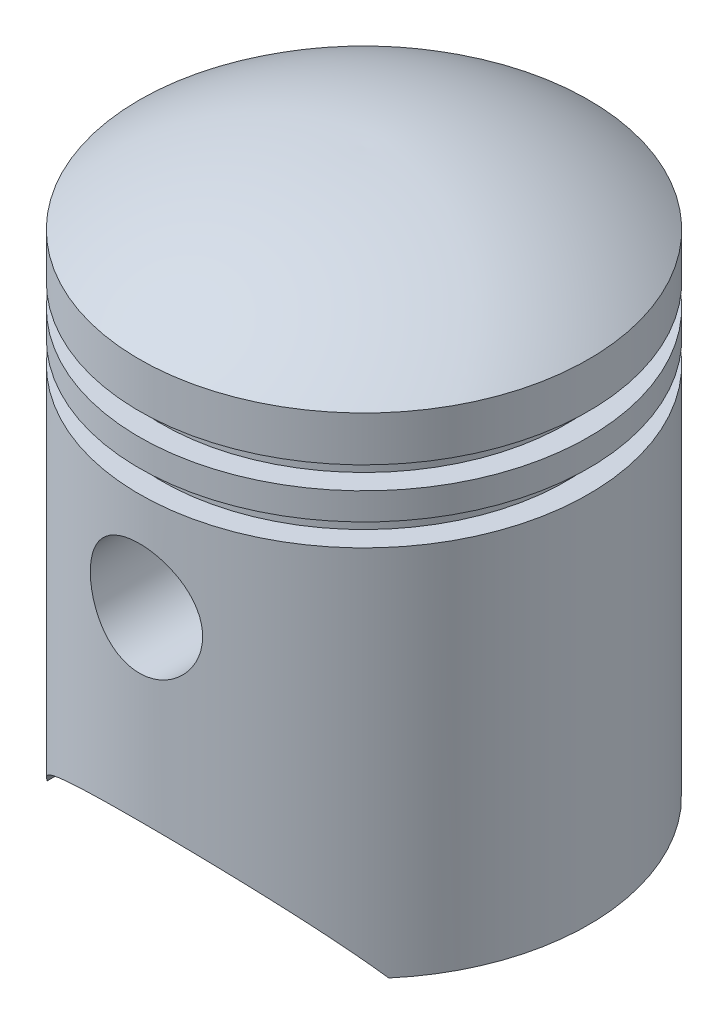
SolidWorks part; units mm, degrees
ref_plane "Front Plane" through (0, 0, 0) normal (0, 0, 1) x (1, 0, 0)
ref_plane "Top Plane" through (0, 0, 0) normal (0, 1, 0) x (1, 0, 0)
ref_plane "Right Plane" through (0, 0, 0) normal (1, 0, 0) x (0, 0, -1)
sketch "Sketch3" plane through (0, 0, 0) normal (0, 0, 1) x (1, 0, 0)
  line L0 (25, 0) -> (25, 41.5)
  line L1 (25, 49.5) -> (22.5, 49.5)
  line L2 (22.5, 49.5) -> (22.5, 47)
  line L3 (22.5, 47) -> (25, 47)
  line L4 (25, 44) -> (22.5, 44)
  line L5 (22.5, 44) -> (22.5, 41.5)
  line L6 (22.5, 41.5) -> (25, 41.5)
  line L7 (25, 49.5) -> (25, 54.5)
  line L8 (25, 44) -> (25, 47)
  line L9 (23, 0) -> (23, 39.5)
  line L10 (20.5, 39.5) -> (23, 39.5)
  line L11 (20.5, 45.5) -> (20.5, 39.5)
  line L12 (20.5, 45.5) -> (20.5, 45.5)
  line L13 (20.5, 45.5) -> (20.5, 45.5)
  line L14 (20.5, 45.5) -> (20.5, 45.5)
  line L15 (20.5, 51.5) -> (20.5, 45.5)
  line L16 (23, 51.5) -> (20.5, 51.5)
  line L17 (23, 51.5) -> (23, 53.4845)
  line L18 (25, 0) -> (23, 0)
  line L20 (0, 62.5) -> (0, 60.4994)
  arc A0 (25, 54.5) -> (0, 62.5) centre (0.9839, 22.5121) ccw
  arc A1 (23, 53.4845) -> (0, 60.4994) centre (0.9839, 22.5121) ccw
  arc A2 (23, 53.4845) -> (0.0492, 60.5006) centre (0.9839, 22.5121) ccw construction
  dimension "D4" = 40
  dimension "D1" = 25
  dimension "D2" = 62.5
  dimension "D3" = 54.5
  dimension "D5" = 2.5
  dimension "D6" = 5
  dimension "D7" = 3
  dimension "D8" = 2.5
  dimension "D9" = 2.5
  dimension "D10" = 2
revolve "Revolve1" add sketch "Sketch3" angle 360 about L20
sketch "Sketch4" plane through (0, 0, 0) normal (0, 0, 1) x (1, 0, 0)
  line L0 (-25, 0) -> (25, 0) construction
  line L1 (0, 30.5) -> (0, 62.5) construction
  line L2 (-19, 0) -> (19, 0)
  circle A0 centre (0, 30.5) radius 6.25
  arc A1 (-19, 0) -> (19, 0) centre (0, -13.05) cw
  point P12 (0, 10)
  dimension "D1" = 10
  dimension "D3" = 12.5
  dimension "D2" = 38
  dimension "D4" = 32
extrude "Cut-Extrude1" cut sketch "Sketch4" against normal through all both and the other way through all
sketch "Sketch5" plane through (0, 0, 0) normal (0, 0, 1) x (1, 0, 0)
  circle A0 centre (0, 30.5) radius 7.25
  circle A1 centre (0, 30.5) radius 6.25
  dimension "D1" = 14.5
  dimension "D2" = 12.5
extrude "Boss-Extrude1" add sketch "Sketch5" along normal up to surface (11.9257 mm away) from offset 12
mirror "Mirror1" about plane through (0, 0, 0) normal (0, 0, 1) of "Boss-Extrude1"
